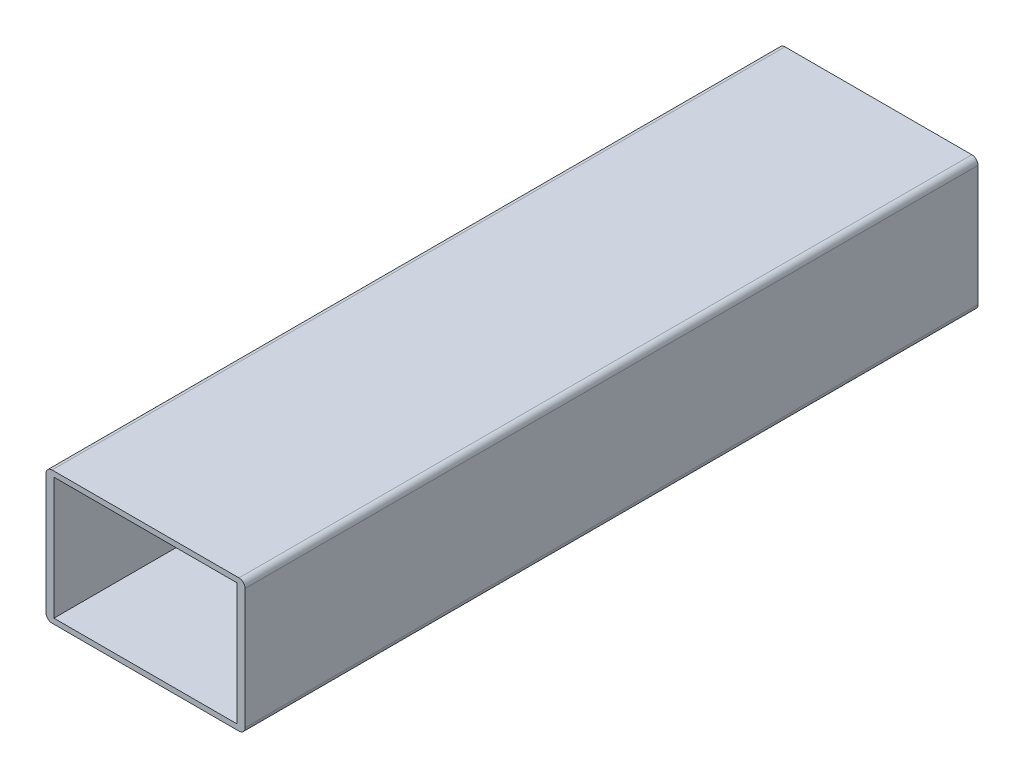
SolidWorks part; units mm, degrees
material "Alloy Steel"
ref_plane "Front Plane" through (0, 0, 0) normal (0, 0, 1) x (1, 0, 0)
ref_plane "Top Plane" through (0, 0, 0) normal (0, 1, 0) x (1, 0, 0)
ref_plane "Right Plane" through (0, 0, 0) normal (1, 0, 0) x (0, 0, -1)
sketch "Sketch1" plane through (0, 0, 0) normal (0, 0, 1) x (1, 0, 0)
  line L1 (19.05, -12.7) -> (-19.05, -12.7)
  line L2 (19.05, -12.7) -> (19.05, 12.7)
  line L3 (19.05, 12.7) -> (-19.05, 12.7)
  line L4 (-19.05, -12.7) -> (-19.05, 12.7)
  line L5 (19.05, -12.7) -> (-19.05, 12.7) construction
  line L6 (19.05, 12.7) -> (-19.05, -12.7) construction
  line L7 (19.431, -13.8007) -> (-19.431, -13.8007)
  line L8 (20.701, -12.5307) -> (20.701, 12.5307)
  line L9 (19.431, 13.8007) -> (-19.431, 13.8007)
  line L10 (-20.701, -12.5307) -> (-20.701, 12.5307)
  line L11 (20.701, -13.8007) -> (-20.701, 13.8007) construction
  line L12 (20.701, 13.8007) -> (-20.701, -13.8007) construction
  arc A0 (-19.431, 13.8007) -> (-20.701, 12.5307) centre (-19.431, 12.5307) ccw
  arc A1 (-20.701, -12.5307) -> (-19.431, -13.8007) centre (-19.431, -12.5307) ccw
  arc A2 (19.431, -13.8007) -> (20.701, -12.5307) centre (19.431, -12.5307) ccw
  arc A3 (20.701, 12.5307) -> (19.431, 13.8007) centre (19.431, 12.5307) ccw
  point P0 (0, 0)
  point P6 (0, 0)
  dimension "D4" = 1.27
  dimension "D5" = 1.27
  dimension "D1" = 25.4
  dimension "D2" = 38.1
  dimension "D3" = 1.651
extrude "Boss-Extrude1" add sketch "Sketch1" along normal blind 152.4
